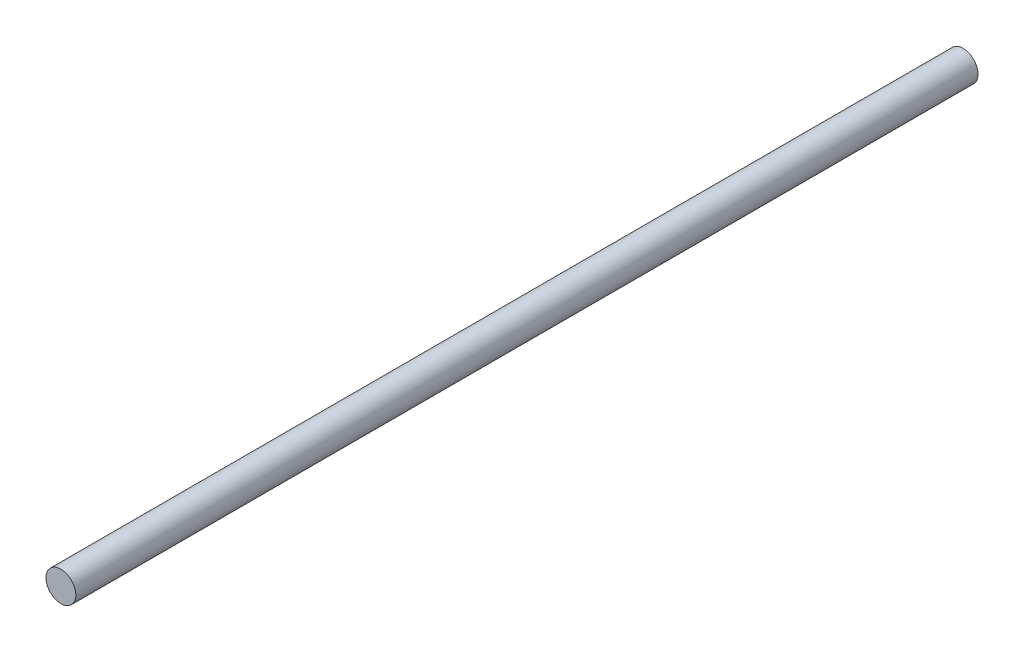
SolidWorks part; units mm, degrees
ref_plane "Front" through (0, 0, 0) normal (0, 0, 1) x (1, 0, 0)
ref_plane "Top" through (0, 0, 0) normal (0, 1, 0) x (1, 0, 0)
ref_plane "Right" through (0, 0, 0) normal (1, 0, 0) x (0, 0, -1)
sketch "Sketch1" plane through (0, 0, 0) normal (0, 0, 1) x (1, 0, 0)
  circle A0 centre (0, 0) radius 4
  dimension "D1" = 8
extrude "Boss-Extrude1" add sketch "Sketch1" along normal blind 241.52
equation "\"yplate-height\"= 200mm"
equation "\"linear-thread-dia\"= 8mm ' Diameter of the metal threaded rod used on the X Axis"
equation "\"material-thickness\"= 12.4mm"
equation "\"nut_depth\"= 4.76mm"
equation "\"stepper_clearance\"= 32mm"
equation "\"rod_length_yaxis\"= \"yplate-height\" + ( \"nut_depth\" * 2 ) + \"stepper_clearance\""
equation "\"D1@Boss-Extrude1\"= \"rod_length_yaxis\""
equation "\"D1@Sketch1\"= \"linear-thread-dia\""
